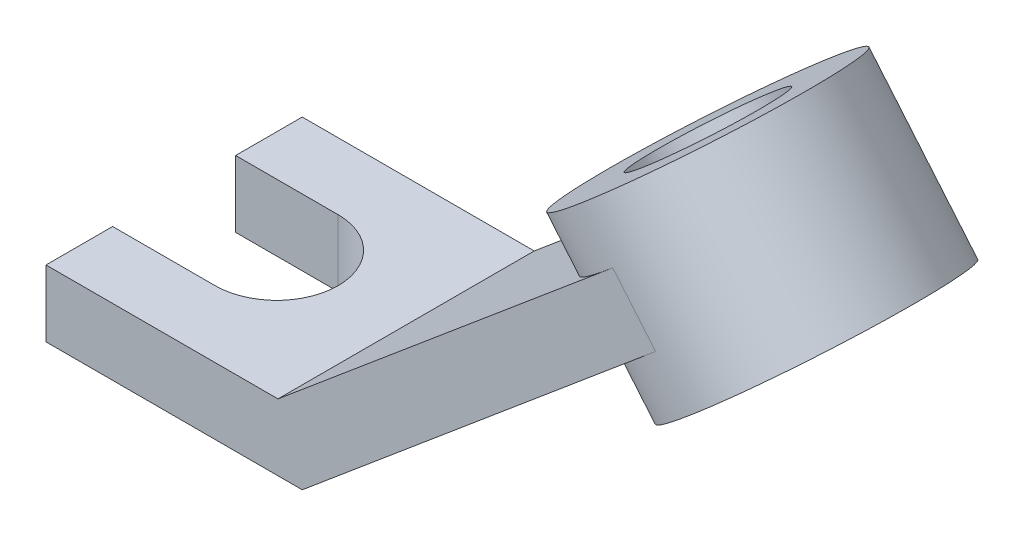
SolidWorks part; units mm, degrees
ref_plane "정면" through (0, 0, 0) normal (0, 0, 1) x (1, 0, 0)
ref_plane "윗면" through (0, 0, 0) normal (0, 1, 0) x (1, 0, 0)
ref_plane "우측면" through (0, 0, 0) normal (1, 0, 0) x (0, 0, -1)
sketch "Sketch1" plane through (0, 0, 0) normal (0, 0, 1) x (1, 0, 0)
  line L0 (0, 0) -> (47.6342, 0)
  line L1 (47.6342, 0) -> (114.7659, 56.3302)
  line L2 (0, -6.5) -> (50, -6.5)
  line L3 (50, -6.5) -> (118.944, 51.3509)
  line L4 (0, 6.5) -> (45.2684, 6.5)
  line L5 (45.2684, 6.5) -> (110.5878, 61.3095)
  line L6 (0, -6.5) -> (0, 6.5)
  line L7 (118.944, 51.3509) -> (110.5878, 61.3095)
  line L8 (125.3719, 43.6904) -> (104.1599, 68.9699)
  point P10 (114.7659, 56.3302)
  dimension "D1" = 140
  dimension "D4" = 50
  dimension "D5" = 90
  dimension "D6" = 33
  dimension "D2" = 6.5
  dimension "D3" = 6.5
extrude "Boss-Extrude1" add sketch "Sketch1" along normal blind 50 contours L1 L7 L5 L4 L6 L0 | L3 L7 L1 L0 L6 L2
sketch "Sketch3" plane through (15.5032, -18.476, 0) normal (-0.6428, 0.766, 0) x (0.766, 0.6428, 0)
  line L0 (124.1241, -50) -> (124.1241, 0) construction
  circle A0 centre (124.1241, -25) radius 25
extrude "Boss-Extrude2" add sketch "Sketch3" along normal blind 10 and the other way blind 23
sketch "Sketch5" plane through (0, 6.5, 0) normal (0, 1, 0) x (1, 0, 0)
  line L0 (0, -25) -> (20, -25) construction
  line L1 (0, -50) -> (0, 0) construction
  line L2 (0, -13) -> (20, -13)
  line L3 (0, -37) -> (20, -37)
  arc A0 (0, -13) -> (0, -37) centre (0, -25) ccw
  arc A1 (20, -37) -> (20, -13) centre (20, -25) ccw
  point P4 (10, -25)
  dimension "D1" = 20
  dimension "D2" = 24
extrude "Cut-Extrude1" cut sketch "Sketch5" against normal up to next
sketch "Sketch6" plane through (9.0753, -10.8155, 0) normal (-0.6428, 0.766, 0) x (0.766, 0.6428, 0)
  circle A0 centre (124.1241, -25) radius 13
  dimension "D1" = 26
extrude "Cut-Extrude2" cut sketch "Sketch6" against normal through all
